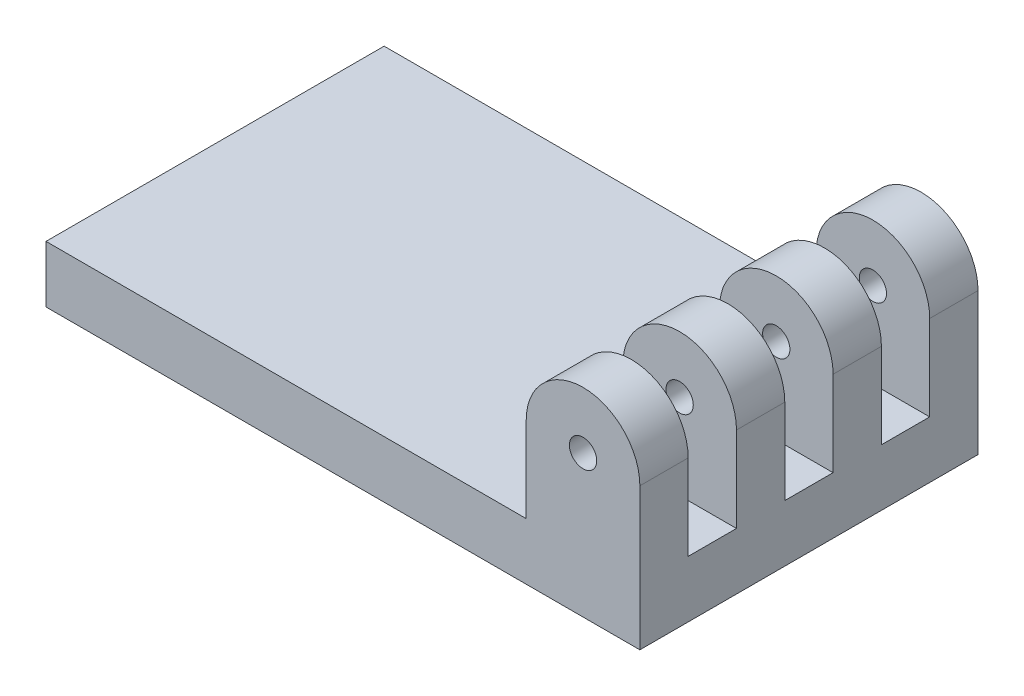
SolidWorks part; units mm, degrees
ref_plane "Front Plane" through (0, 0, 0) normal (0, 0, 1) x (1, 0, 0)
ref_plane "Top Plane" through (0, 0, 0) normal (0, 1, 0) x (1, 0, 0)
ref_plane "Right Plane" through (0, 0, 0) normal (1, 0, 0) x (0, 0, -1)
sketch "Sketch1" plane through (0, 0, 0) normal (0, 1, 0) x (1, 0, 0)
  line L1 (-52.25, 29.75) -> (52.25, 29.75)
  line L2 (-52.25, 29.75) -> (-52.25, -29.75)
  line L3 (-52.25, -29.75) -> (52.25, -29.75)
  line L4 (52.25, 29.75) -> (52.25, -29.75)
  line L5 (-52.25, 29.75) -> (52.25, -29.75) construction
  line L6 (-52.25, -29.75) -> (52.25, 29.75) construction
  point P0 (0, 0)
  dimension "D1" = 104.5
  dimension "D2" = 59.5
extrude "Boss-Extrude1" add sketch "Sketch1" along normal blind 10
sketch "Sketch3" plane through (0, 0, 0) normal (0, 0, 1) x (1, 0, 0)
  line L0 (52.25, 10) -> (52.25, 25)
  line L1 (52.25, 10) -> (32.25, 10)
  line L2 (-52.25, 10) -> (52.25, 10) construction
  line L3 (32.25, 10) -> (32.25, 25)
  arc A0 (32.25, 25) -> (52.25, 25) centre (42.25, 25) cw
  dimension "D1" = 15
  dimension "D2" = 20
extrude "Boss-Extrude2" add sketch "Sketch3" along normal up to surface and the other way up to surface up to face at (0, 5, 29.75) other way up to face at (0, 5, -29.75)
sketch "Sketch4" plane through (0, 10, 0) normal (0, 1, 0) x (1, 0, 0)
  line L0 (32.25, -29.75) -> (32.25, 29.75) construction
  line L1 (32.25, 21.25) -> (52.25, 21.25)
  line L2 (32.25, 21.25) -> (32.25, 12.75)
  line L3 (32.25, 12.75) -> (52.25, 12.75)
  line L4 (52.25, 21.25) -> (52.25, 12.75)
  line L5 (52.25, -29.75) -> (52.25, 29.75) construction
  line L6 (42.25, 29.75) -> (42.25, 21.25) construction
  line L7 (32.25, 4.25) -> (52.25, 4.25)
  line L8 (32.25, 4.25) -> (32.25, -4.25)
  line L9 (32.25, -4.25) -> (52.25, -4.25)
  line L10 (52.25, 4.25) -> (52.25, -4.25)
  line L11 (32.25, -12.75) -> (52.25, -12.75)
  line L12 (32.25, -12.75) -> (32.25, -21.25)
  line L13 (32.25, -21.25) -> (52.25, -21.25)
  line L14 (52.25, -12.75) -> (52.25, -21.25)
  line L15 (52.25, 29.75) -> (32.25, 29.75) construction
  line L16 (42.25, 12.75) -> (42.25, 4.25) construction
  line L17 (42.25, -4.25) -> (42.25, -12.75) construction
  line L18 (42.25, -21.25) -> (42.25, -29.75) construction
  line L19 (32.25, -29.75) -> (52.25, -29.75) construction
extrude "Cut-Extrude1" cut sketch "Sketch4" along normal through all
sketch "Sketch7" plane through (0, 0, 29.75) normal (0, 0, 1) x (1, 0, 0)
  circle A1 centre (42.25, 25) radius 10
  point P0 (42.25, 25)
  point P9 (42.25, 25)
hole_wizard "M4 Clearance Hole1" positions "Sketch7" profile "Sketch6" hole size "M4" standard "ANSI Metric" end condition through all
sketch "Sketch6" plane through (42.25, 25, 29.75) normal (1, 0, 0) x (0, -1, 0)
  line L0 (0, 0) -> (0, 59.5)
  line L1 (0, 59.5) -> (2.4, 59.5)
  line L2 (2.4, 59.5) -> (2.4, 0)
  line L5 (2.4, 0) -> (0, 0)
  line L11 (0, -6.35) -> (0, 107.95) construction
  dimension "Thru Hole Dia." = 4.8
  dimension "Thru Hole Depth" = 59.5
